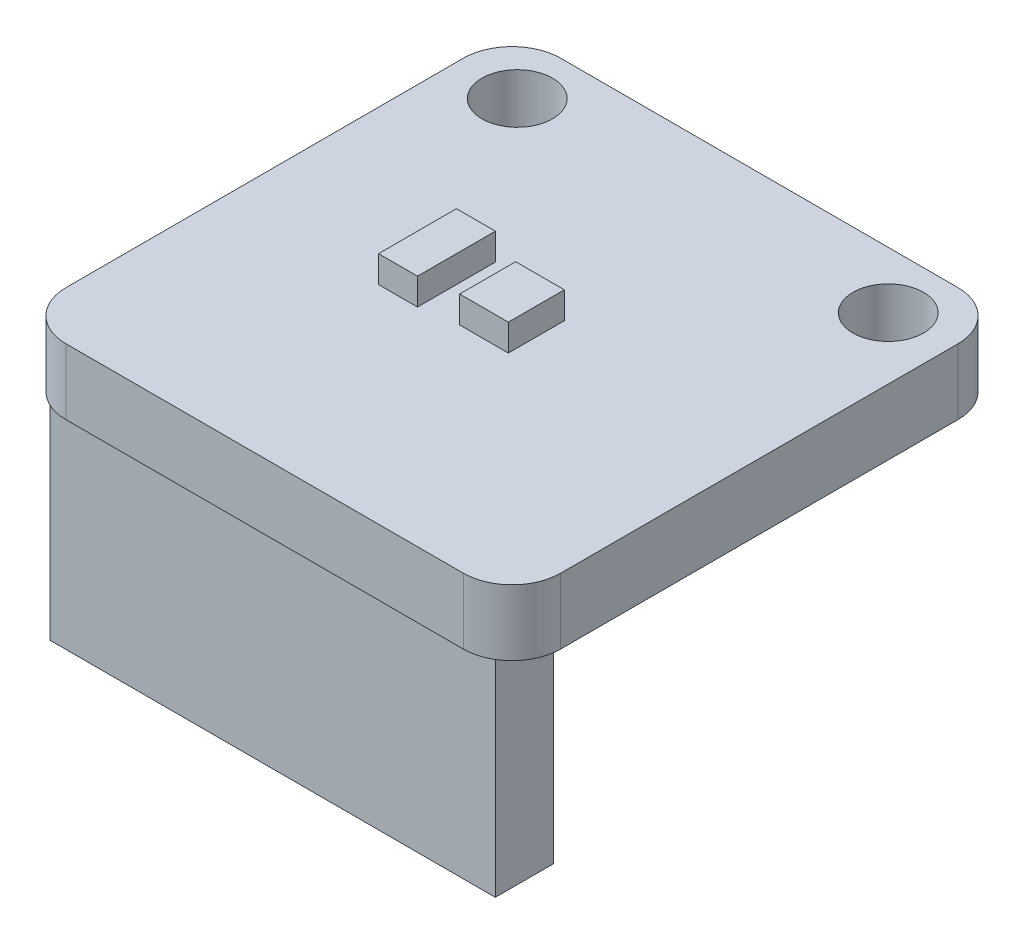
SolidWorks part; units mm, degrees
ref_plane "Plan de face" through (0, 0, 0) normal (0, 0, 1) x (1, 0, 0)
ref_plane "Plan de dessus" through (0, 0, 0) normal (0, 1, 0) x (1, 0, 0)
ref_plane "Plan de droite" through (0, 0, 0) normal (1, 0, 0) x (0, 0, -1)
sketch "Esquisse1" plane through (0, 0, 0) normal (0, 1, 0) x (1, 0, 0)
  line L1 (-10.16, -10.16) -> (10.16, -10.16)
  line L2 (-10.16, -10.16) -> (-10.16, 10.16)
  line L3 (-10.16, 10.16) -> (10.16, 10.16)
  line L4 (10.16, -10.16) -> (10.16, 10.16)
  point P4 (-10.16, 0)
  point P5 (0, 10.16)
  dimension "D1" = 20.32
extrude "Boss.-Extru.1" add sketch "Esquisse1" along normal blind 2.7
hole_wizard "Dégagement M2.51" positions "Esquisse5" profile "Esquisse6" hole size "M2.5" standard "DIN" end condition through all
sketch "Esquisse5" plane through (0, 2.7, 0) normal (0, 1, 0) x (1, 0, 0)
  line L1 (0, 0) -> (0, 3.6205) construction
  point P8 (-7.62, 7.835)
  point P16 (7.62, 7.835)
  dimension "D1" = 15.24
sketch "Esquisse6" plane through (-7.62, 2.7, -7.835) normal (1, 0, 0) x (0, 0, 1)
  line L0 (0, 0) -> (0, 2.7)
  line L1 (0, 2.7) -> (1.45, 2.7)
  line L2 (1.45, 2.7) -> (1.45, 0)
  line L5 (1.45, 0) -> (0, 0)
  line L11 (0, -6.35) -> (0, 107.95) construction
  dimension "Diamètre du perçage jusqu'au prochain" = 2.9
  dimension "Profondeur du perçage jusqu'au prochain" = 2.7
sketch "Esquisse7" plane through (0, 2.7, 0) normal (0, 1, 0) x (1, 0, 0)
  line L0 (10.16, -10.16) -> (10.16, 10.16) construction
  line L1 (-0.746, 0.896) -> (1.254, 0.896)
  line L2 (-0.746, 0.896) -> (-0.746, -1.404)
  line L3 (-0.746, -1.404) -> (1.254, -1.404)
  line L4 (1.254, 0.896) -> (1.254, -1.404)
  line L5 (-3.848, 1.566) -> (-2.248, 1.566)
  line L6 (-3.848, 1.566) -> (-3.848, -1.634)
  line L7 (-3.848, -1.634) -> (-2.248, -1.634)
  line L8 (-2.248, 1.566) -> (-2.248, -1.634)
  line L9 (10.16, 10.16) -> (-10.16, 10.16) construction
  point P9 (0.254, -1.404)
  point P12 (-3.048, -1.634)
  point P13 (1.254, -0.254)
  dimension "D1" = 9.906
  dimension "D2" = 3.302
  dimension "D3" = 10.414
  dimension "D4" = 2.3
  dimension "D5" = 2
  dimension "D6" = 3.2
  dimension "D7" = 1.6
  dimension "D8" = 0.67
extrude "Boss.-Extru.3" add sketch "Esquisse7" along normal blind 1.1
sketch "Esquisse3" plane through (0, 0, 0) normal (0, 1, 0) x (1, 0, 0)
  line L0 (-10.16, -10.16) -> (10.16, -10.16) construction
  line L7 (-9.15, -7.436) -> (9.15, -7.436)
  line L8 (-9.15, -7.436) -> (-9.15, -9.836)
  line L9 (-9.15, -9.836) -> (9.15, -9.836)
  line L10 (9.15, -7.436) -> (9.15, -9.836)
  point P4 (0, -7.436)
  point P7 (9.15, -8.636)
  dimension "D1" = 2.4
  dimension "D2" = 18.3
  dimension "D3" = 1.524
extrude "Boss.-Extru.2" add sketch "Esquisse3" against normal blind 8.5
fillet "Congé1" radius 2 4 edges at (-10.16, 1.35, 10.16) (10.16, 1.35, 10.16) (10.16, 1.35, -10.16) (-10.16, 1.35, -10.16)
